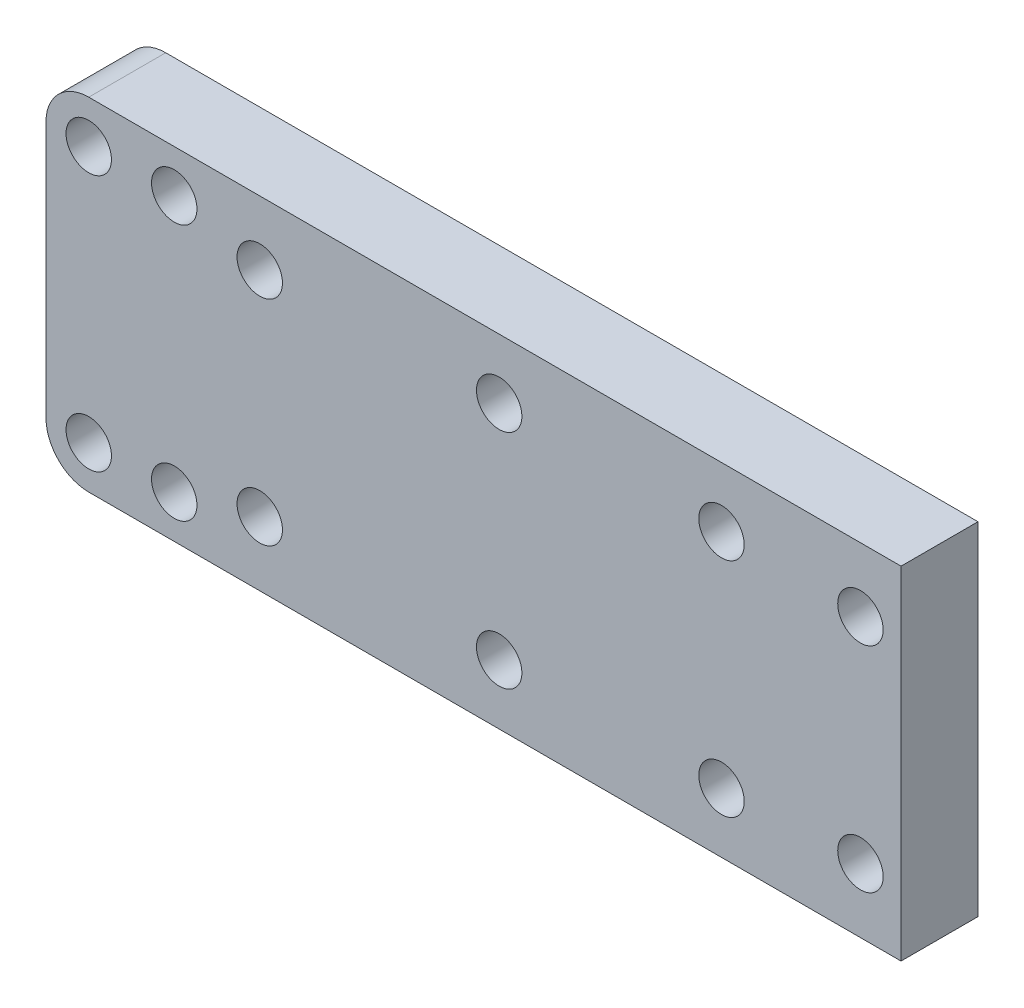
SolidWorks part; units mm, degrees
ref_plane "Front Plane" through (0, 0, 0) normal (0, 0, 1) x (1, 0, 0)
ref_plane "Top Plane" through (0, 0, 0) normal (0, 1, 0) x (1, 0, 0)
ref_plane "Right Plane" through (0, 0, 0) normal (1, 0, 0) x (0, 0, -1)
sketch "Sketch2" plane through (0, 0, 0) normal (0, 0, 1) x (1, 0, 0)
  line L1 (-48.1166, 24.4284) -> (78.8834, 24.4284)
  line L2 (-48.1166, 24.4284) -> (-48.1166, -26.3716)
  line L3 (-48.1166, -26.3716) -> (78.8834, -26.3716)
  line L4 (78.8834, 24.4284) -> (78.8834, -26.3716)
  dimension "D1" = 50.8
  dimension "D2" = 127
extrude "Boss-Extrude1" add sketch "Sketch2" along normal blind 11.43
sketch "Sketch3" plane through (0, 0, 0) normal (0, 0, -1) x (-1, 0, 0)
  line L0 (-69.9934, 15.5384) -> (-19.1934, 15.5384) construction
  line L1 (-69.9934, 18.8404) -> (-19.1934, 18.8404)
  line L2 (-69.9934, 12.2364) -> (-19.1934, 12.2364)
  line L3 (-69.9934, -17.4816) -> (-19.1934, -17.4816) construction
  line L4 (-69.9934, -14.1796) -> (-19.1934, -14.1796)
  line L5 (-69.9934, -20.7836) -> (-19.1934, -20.7836)
  line L6 (-78.8834, -26.3716) -> (-78.8834, 24.4284) construction
  line L7 (-78.8834, 24.4284) -> (48.1166, 24.4284) construction
  line L8 (48.1166, -26.3716) -> (-78.8834, -26.3716) construction
  arc A0 (-69.9934, 18.8404) -> (-69.9934, 12.2364) centre (-69.9934, 15.5384) ccw
  arc A1 (-19.1934, 12.2364) -> (-19.1934, 18.8404) centre (-19.1934, 15.5384) ccw
  arc A2 (-69.9934, -14.1796) -> (-69.9934, -20.7836) centre (-69.9934, -17.4816) ccw
  arc A3 (-19.1934, -20.7836) -> (-19.1934, -14.1796) centre (-19.1934, -17.4816) ccw
  point P2 (-44.5934, 15.5384)
  point P7 (-44.5934, -17.4816)
  dimension "D5" = 3.302
  dimension "D6" = 3.302
  dimension "D7" = 50.8
  dimension "D1" = 8.89
  dimension "D2" = 8.89
  dimension "D3" = 8.89
  dimension "D4" = 8.89
  dimension "D8" = 50.8
extrude "Cut-Extrude1" [suppressed] cut sketch "Sketch3" against normal through all
sketch "Sketch4" [suppressed] plane through (0, 0, 0) normal (0, 0, -1) x (-1, 0, 0)
  line L0 (48.1166, 24.4284) -> (48.1166, -39.0716) construction
  line L1 (-91.5834, 24.4284) -> (48.1166, 24.4284) construction
  circle A0 centre (22.7166, -0.9716) radius 3.917
  dimension "D1" = 25.4
  dimension "D2" = 25.4
hole_wizard "5/16 (0.3125) Diameter Hole1" [suppressed] positions "3DSketch1" profile "Sketch5" hole size "5/16" standard "ANSI Inch"
sketch3d "3DSketch1" [suppressed]
  point P0 (-22.7166, -0.9716, 0)
sketch "Sketch5" plane through (-22.7166, -0.9716, 0) normal (1, 0, 0) x (0, 1, 0)
  line L0 (0, 0) -> (0, 11.43)
  line L1 (0, 11.43) -> (3.9687, 11.43)
  line L2 (3.9687, 11.43) -> (3.9688, 0)
  line L5 (3.9688, 0) -> (0, 0)
  line L11 (0, -6.35) -> (0, 107.95) construction
  dimension "Thru Hole Dia." = 7.9375
  dimension "Thru Hole Depth" = 11.43
fillet "Fillet1" radius 6.35 2 edges at (-48.1166, -26.3716, 5.715) (-48.1166, 24.4284, 5.715)
sketch "Sketch6" [suppressed] plane through (0, 0, 0) normal (0, 0, -1) x (-1, 0, 0)
  circle A0 centre (-69.9934, 15.5384) radius 0.9231
  circle A1 centre (-69.9934, -17.4816) radius 0.7051
hole_wizard "17/64 (0.26563) Diameter Hole1" [suppressed] positions "3DSketch2" profile "Sketch7" hole size "17/64" standard "ANSI Inch"
sketch3d "3DSketch2" [suppressed]
  point P0 (69.9934, 15.5384, 0)
  point P3 (69.9934, -17.4816, 0)
sketch "Sketch7" plane through (69.9934, 15.5384, 0) normal (1, 0, 0) x (0, 1, 0)
  line L0 (0, 0) -> (0, 11.43)
  line L1 (0, 11.43) -> (3.3735, 11.43)
  line L2 (3.3735, 11.43) -> (3.3735, 0)
  line L5 (3.3735, 0) -> (0, 0)
  line L11 (0, -6.35) -> (0, 107.95) construction
  dimension "Thru Hole Dia." = 6.747
  dimension "Thru Hole Depth" = 11.43
sketch "Sketch8" plane through (0, 0, 0) normal (0, 0, -1) x (-1, 0, 0)
  line L0 (-78.8834, 24.4284) -> (41.7666, 24.4284) construction
  line L1 (-78.8834, -26.3716) -> (-78.8834, 24.4284) construction
  line L2 (41.7666, -26.3716) -> (-78.8834, -26.3716) construction
  circle A0 centre (-19.1934, 15.5384) radius 0.4971
  circle A1 centre (-19.1934, -17.4816) radius 0.4447
  circle A2 centre (-52.2134, 15.5384) radius 1.397
  circle A3 centre (-52.2134, -17.4816) radius 0.7487
  dimension "D1" = 8.89
  dimension "D2" = 59.69
  dimension "D3" = 8.89
  dimension "D4" = 59.69
  dimension "D5" = 8.89
  dimension "D6" = 33.02
  dimension "D7" = 8.89
  dimension "D8" = 33.02
hole_wizard "17/64 (0.26563) Diameter Hole2" positions "3DSketch3" profile "Sketch9" hole size "17/64" standard "ANSI Inch" end condition through all
sketch3d "3DSketch3"
  point P0 (52.2134, 15.5384, 0)
  point P3 (19.1934, 15.5384, 0)
  point P6 (19.1934, -17.4816, 0)
  point P9 (52.2134, -17.4816, 0)
sketch "Sketch9" plane through (52.2134, 15.5384, 0) normal (1, 0, 0) x (0, 1, 0)
  line L0 (0, 0) -> (0, 11.43)
  line L1 (0, 11.43) -> (3.3735, 11.43)
  line L2 (3.3735, 11.43) -> (3.3735, 0)
  line L5 (3.3735, 0) -> (0, 0)
  line L11 (0, -6.35) -> (0, 107.95) construction
  dimension "Thru Hole Dia." = 6.747
  dimension "Thru Hole Depth" = 11.43
sketch "Sketch10" plane through (0, 0, 0) normal (0, 0, -1) x (-1, 0, 0)
  line L0 (-78.8834, -26.3716) -> (-78.8834, 24.4284) construction
  line L1 (-78.8834, 24.4284) -> (41.7666, 24.4284) construction
  line L2 (41.7666, -26.3716) -> (-78.8834, -26.3716) construction
  circle A0 centre (16.3666, 14.9034) radius 2.9996
  circle A1 centre (16.3666, -16.8466) radius 3.8699
  dimension "D1" = 95.25
  dimension "D2" = 95.25
  dimension "D3" = 9.525
  dimension "D4" = 9.525
hole_wizard "17/64 (0.26563) Diameter Hole3" positions "3DSketch4" profile "Sketch12" hole size "17/64" standard "ANSI Inch" end condition through all
sketch3d "3DSketch4"
  point P0 (-16.3666, 14.9034, 0)
  point P3 (-16.3666, -16.8466, 0)
sketch "Sketch12" plane through (-16.3666, 14.9034, 0) normal (1, 0, 0) x (0, 1, 0)
  line L0 (0, 0) -> (0, 11.43)
  line L1 (0, 11.43) -> (3.3735, 11.43)
  line L2 (3.3735, 11.43) -> (3.3735, 0)
  line L5 (3.3735, 0) -> (0, 0)
  line L11 (0, -6.35) -> (0, 107.95) construction
  dimension "Thru Hole Dia." = 6.747
  dimension "Thru Hole Depth" = 11.43
sketch "Sketch13" plane through (0, 0, 0) normal (0, 0, -1) x (-1, 0, 0)
  point P0 (-72.8509, -16.8466)
  point P1 (-72.8509, 14.9034)
hole_wizard "17/64 (0.26563) Diameter Hole4" positions "3DSketch5" profile "Sketch14" hole size "17/64" standard "ANSI Inch" end condition through all
sketch3d "3DSketch5"
  point P0 (72.8509, -16.8466, 0)
  point P3 (72.8509, 14.9034, 0)
sketch "Sketch14" plane through (72.8509, -16.8466, 0) normal (1, 0, 0) x (0, 1, 0)
  line L0 (0, 0) -> (0, 11.43)
  line L1 (0, 11.43) -> (3.3735, 11.43)
  line L2 (3.3735, 11.43) -> (3.3735, 0)
  line L5 (3.3735, 0) -> (0, 0)
  line L11 (0, -6.35) -> (0, 107.95) construction
  dimension "Thru Hole Dia." = 6.747
  dimension "Thru Hole Depth" = 11.43
sketch "Sketch15" plane through (0, 0, 0) normal (0, 0, -1) x (-1, 0, 0)
  line L0 (48.1166, 18.0784) -> (48.1166, -20.0216) construction
  line L1 (41.7666, -26.3716) -> (-78.8834, -26.3716) construction
  line L2 (-78.8834, 24.4284) -> (41.7666, 24.4284) construction
  point P0 (41.7666, -20.0216)
  point P1 (29.0666, -20.0216)
  point P2 (41.7666, 18.0784)
  point P3 (29.0666, 18.0784)
  dimension "D1" = 6.35
  dimension "D2" = 6.35
  dimension "D3" = 6.35
  dimension "D4" = 12.7
  dimension "D5" = 6.35
  dimension "D6" = 6.35
  dimension "D7" = 6.35
  dimension "D8" = 12.7
hole_wizard "17/64 (0.26563) Diameter Hole6" positions "3DSketch7" profile "Sketch17" hole size "17/64" standard "ANSI Inch" end condition through all
sketch3d "3DSketch7"
  point P0 (-29.0666, 18.0784, 0)
  point P3 (-41.7666, 18.0784, 0)
  point P6 (-41.7666, -20.0216, 0)
  point P9 (-29.0666, -20.0216, 0)
sketch "Sketch17" plane through (-29.0666, 18.0784, 0) normal (1, 0, 0) x (0, 1, 0)
  line L0 (0, 0) -> (0, 11.43)
  line L1 (0, 11.43) -> (3.3735, 11.43)
  line L2 (3.3735, 11.43) -> (3.3735, 0)
  line L5 (3.3735, 0) -> (0, 0)
  line L11 (0, -6.35) -> (0, 107.95) construction
  dimension "Thru Hole Dia." = 6.747
  dimension "Thru Hole Depth" = 11.43
